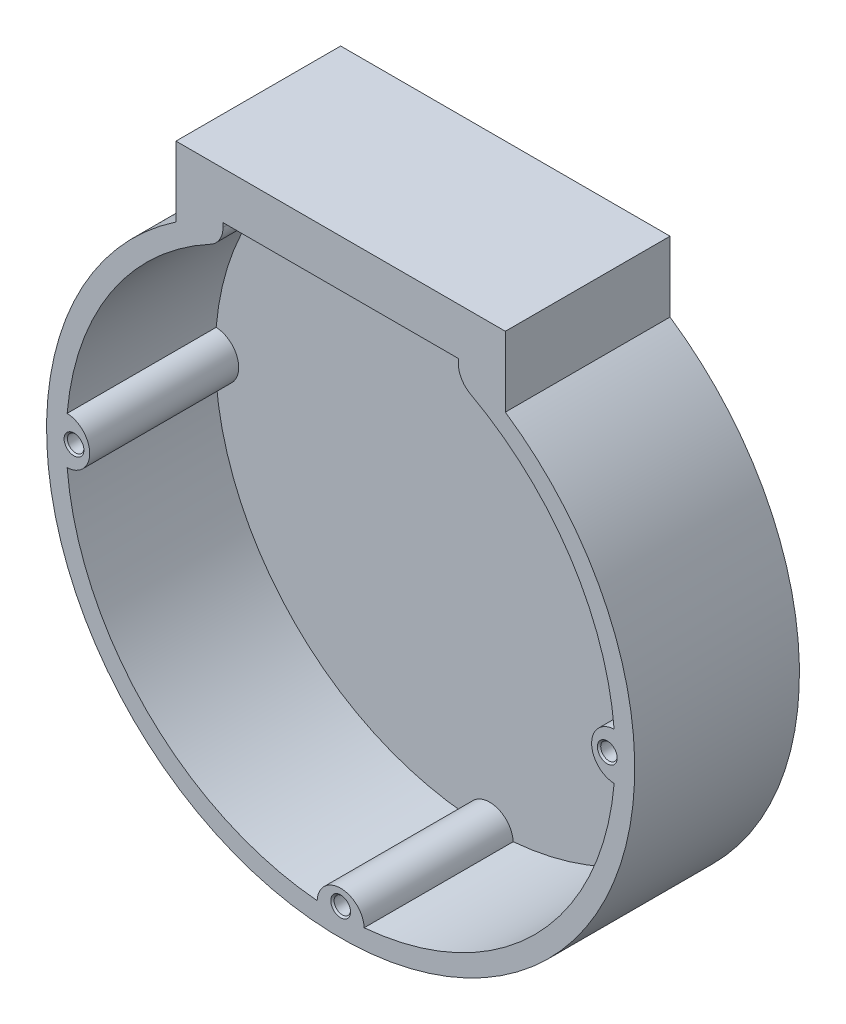
SolidWorks part; units mm, degrees
ref_plane "前视基准面" through (0, 0, 0) normal (0, 0, 1) x (1, 0, 0)
ref_plane "上视基准面" through (0, 0, 0) normal (0, 1, 0) x (1, 0, 0)
ref_plane "右视基准面" through (0, 0, 0) normal (1, 0, 0) x (0, 0, -1)
sketch "草图1" plane through (0, 0, 0) normal (0, 0, 1) x (1, 0, 0)
  line L0 (-194.7082, 0) -> (229.8964, 0) construction
  line L1 (0, 118.2049) -> (0, -143.8723) construction
  line L2 (-42, 62.1369) -> (-42, 80)
  line L3 (-42, 80) -> (42, 80)
  line L4 (42, 80) -> (42, 62.1369)
  arc A1 (-42, 62.1369) -> (42, 62.1369) centre (0, 0) ccw
  dimension "D1" = 75
  dimension "D2" = 84
  dimension "D3" = 80
extrude "凸台-拉伸1" add sketch "草图1" along normal blind 42
sketch "草图2" plane through (0, 0, 42) normal (0, 0, 1) x (1, 0, 0)
  line L0 (0, 113.2479) -> (0, -99.1672) construction
  line L1 (-102.656, 0) -> (110.3668, 0) construction
  line L2 (-30, 66.9328) -> (-30, 68)
  line L3 (-30, 68) -> (30, 68)
  line L4 (30, 68) -> (30, 66.9328)
  line L5 (42, 80) -> (-42, 80) construction
  arc A1 (-33.1579, 61.6486) -> (-69.7429, 5.9945) centre (0, 0) ccw
  arc A2 (33.1579, 61.6486) -> (30, 66.9328) centre (36, 66.9328) cw
  arc A3 (-33.1579, 61.6486) -> (-30, 66.9328) centre (-36, 66.9328) ccw
  arc A4 (5.9945, -69.7429) -> (-5.9945, -69.7429) centre (0, -70) ccw
  arc A5 (5.9945, -69.7429) -> (69.7429, -5.9945) centre (0, 0) ccw
  arc A6 (-69.7429, -5.9945) -> (-69.7429, 5.9945) centre (-70, 0) ccw
  arc A7 (-69.7429, -5.9945) -> (-5.9945, -69.7429) centre (0, 0) ccw
  arc A8 (69.7429, 5.9945) -> (69.7429, -5.9945) centre (70, 0) ccw
  arc A9 (-5.9945, 69.7429) -> (5.9945, 69.7429) centre (0, 70) ccw [skipped]
  arc A10 (69.7429, 5.9945) -> (33.1579, 61.6486) centre (0, 0) ccw
  point P31 (0, 0)
  dimension "D2" = 70
  dimension "D5" = 6
  dimension "D6" = 6
  dimension "D7" = 6
  dimension "D1" = 212.415
  dimension "D3" = 60
  dimension "D4" = 12
  dimension "D8" = 4
extrude "切除-拉伸1" cut sketch "草图2" against normal blind 38 contours A4 A7 A6 A1 A3 L2 L3 L4 A2 A10 A8 A5
sketch "草图3" plane through (0, 0, 42) normal (0, 0, 1) x (1, 0, 0)
  line L0 (0, 0) -> (0, -68) construction
  point P1 (0, -68)
  dimension "D1" = 68
hole_wizard "M5 螺纹孔1" positions "草图3" profile "草图4" tap size "M5" standard "GB" end condition up to next
sketch "草图4" plane through (0, -68, 42) normal (1, 0, 0) x (0, -1, 0)
  line L0 (0, 0) -> (0, 42)
  line L1 (0, 42) -> (2.1, 42)
  line L2 (2.1, 42) -> (2.1, 0.425)
  line L3 (2.1, 0.425) -> (2.525, 0)
  line L5 (2.525, 0) -> (0, 0)
  line L6 (-2.1, 0.425) -> (-2.525, 0) construction
  line L11 (0, -6.35) -> (0, 107.95) construction
  dimension "通孔螺纹孔钻头直径" = 4.2
  dimension "通孔螺纹孔钻头深度" = 42
  dimension "近端锥形沉头孔直径" = 5.05
  dimension "近端锥形沉头孔角度" = 90
cosmetic thread "孔螺纹线1" parameters "D2"=5
sketch "草图5" plane through (0, 0, 0) normal (0, 1, 0) x (1, 0, 0)
  line L0 (0, 0) -> (0, -45.7518) construction
pattern_circular "阵列(圆周)1" count 4 every 90 about axis through (0, 0, 0) along (0, 0, 1) skipping 2 of "M5 螺纹孔1"
